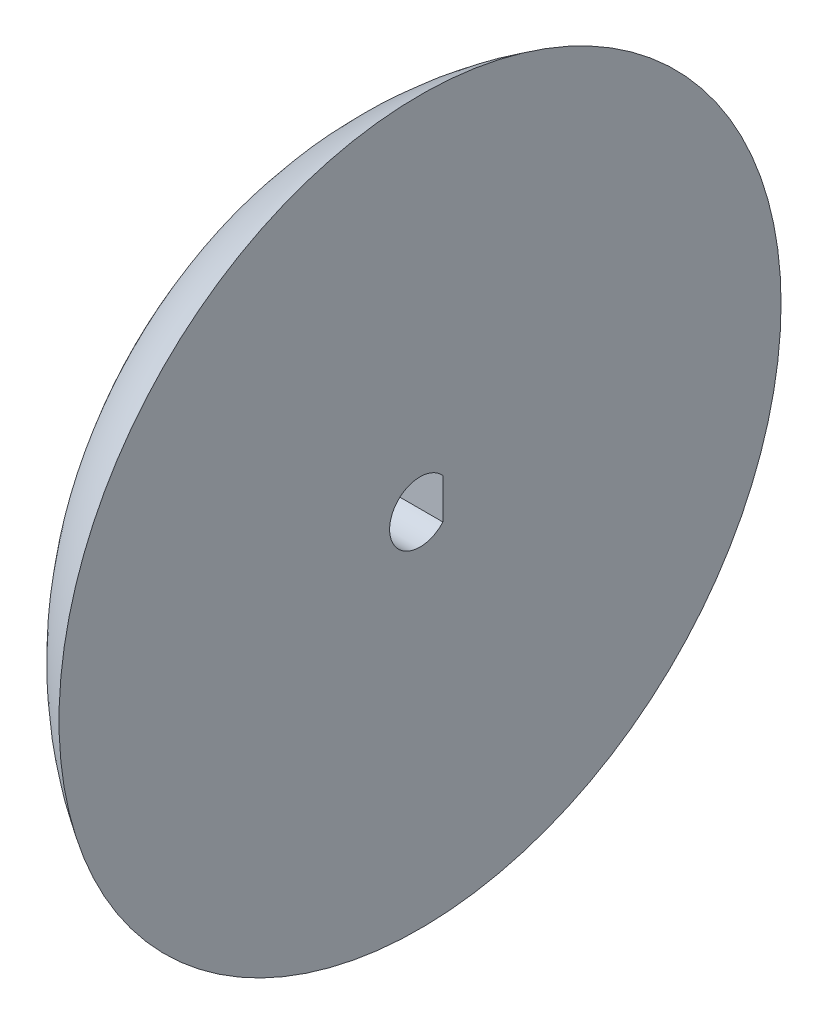
SolidWorks part; units mm, degrees
ref_plane "Alzado" through (0, 0, 0) normal (0, 0, 1) x (1, 0, 0)
ref_plane "Planta" through (0, 0, 0) normal (0, 1, 0) x (1, 0, 0)
ref_plane "Vista lateral" through (0, 0, 0) normal (1, 0, 0) x (0, 0, -1)
sketch "Croquis1" plane through (0, 0, 0) normal (0, 0, 1) x (1, 0, 0)
  line L11 (3.3508, 2.2155) -> (-4.3514, 2.2155)
  line L13 (3.3508, 21.1947) -> (3.3508, 2.2155)
  line L14 (-4.3514, 2.2155) -> (-4.3514, 7.5146)
  arc A3 (3.3508, 21.1947) -> (-4.3514, 7.5146) centre (11.6486, 7.5146) ccw
revolve "Revolución2" add sketch "Croquis1" angle 360 about L11
sketch "Croquis2" plane through (3.3508, 0, 0) normal (1, 0, 0) x (0, 0, -1)
  line L0 (0, 21.1947) -> (0, 2.2155) construction
  line L1 (0, 2.2155) -> (1.2, 2.2155) construction
  line L2 (1.2, 3.2738) -> (1.2, 1.1572)
  circle A0 centre (0, 2.2155) radius 18.9793 construction
  arc A1 (1.2, 3.2738) -> (1.2, 1.1572) centre (0, 2.2155) ccw
  dimension "D1" = 3.2
extrude "Cortar-Extruir1" cut sketch "Croquis2" against normal blind 7
